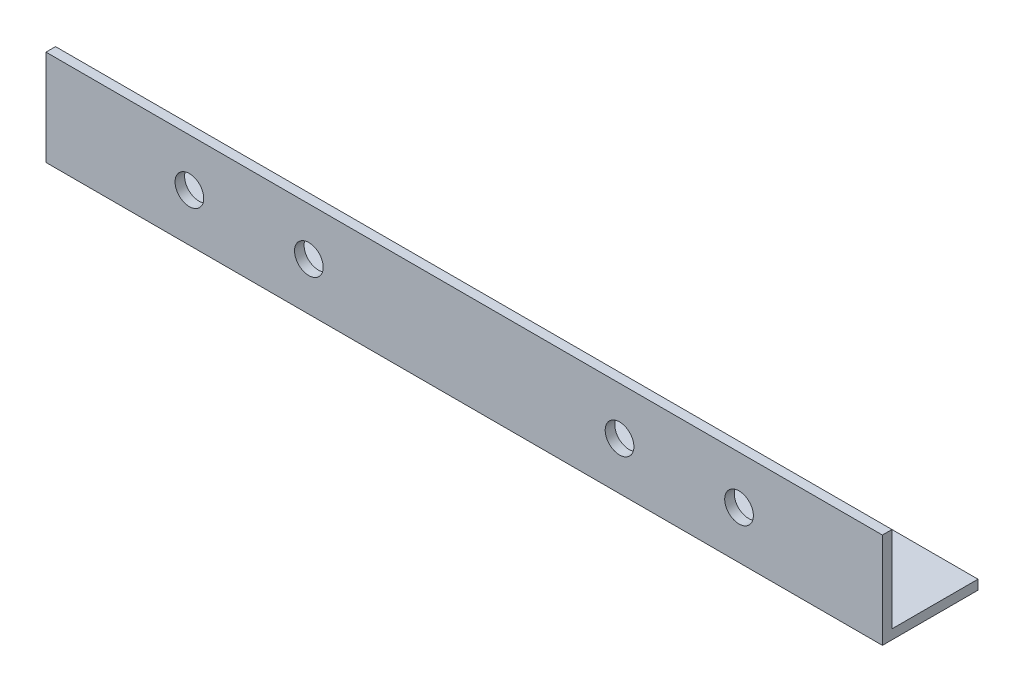
SolidWorks part; units mm, degrees
ref_plane "Front Plane" through (0, 0, 0) normal (0, 0, 1) x (1, 0, 0)
ref_plane "Top Plane" through (0, 0, 0) normal (0, 1, 0) x (1, 0, 0)
ref_plane "Right Plane" through (0, 0, 0) normal (1, 0, 0) x (0, 0, -1)
sketch "Эскиз1" plane through (0, 0, 0) normal (1, 0, 0) x (0, 0, -1)
  line L0 (0, 0) -> (0, 40)
  line L1 (0, 40) -> (4, 40)
  line L2 (4, 40) -> (4, 4)
  line L3 (4, 4) -> (40, 4)
  line L4 (40, 4) -> (40, 0)
  line L5 (40, 0) -> (0, 0)
  dimension "D1" = 40
  dimension "D2" = 40
  dimension "D3" = 4
  dimension "D4" = 4
extrude "Бобышка-Вытянуть1" add sketch "Эскиз1" along normal blind 350
sketch "Эскиз2" plane through (0, 0, 0) normal (0, 0, 1) x (1, 0, 0)
  line L0 (0, 40) -> (0, 0) construction
  line L1 (350, 40) -> (0, 40) construction
  circle A0 centre (60, 20) radius 6
  dimension "D1" = 12
  dimension "D2" = 60
  dimension "D3" = 20
extrude "Вырез-Вытянуть1" cut sketch "Эскиз2" against normal through all
sketch "Эскиз3" plane through (0, 0, 0) normal (0, 0, 1) x (1, 0, 0)
  line L0 (350, 40) -> (0, 40) construction
  line L1 (350, 40) -> (350, 0) construction
  circle A0 centre (290, 20) radius 6
  dimension "D1" = 20
  dimension "D2" = 60
extrude "Вырез-Вытянуть2" cut sketch "Эскиз3" against normal through all
sketch "Эскиз4" plane through (0, 0, 0) normal (0, 0, 1) x (1, 0, 0)
  line L0 (350, 40) -> (0, 40) construction
  line L2 (0, 40) -> (0, 0) construction
  circle A0 centre (240, 20) radius 6
  point P6 (0, 15.3148)
  dimension "D1" = 20
  dimension "D2" = 240
extrude "Вырез-Вытянуть3" cut sketch "Эскиз4" against normal through all
sketch "Эскиз6" plane through (0, 0, 0) normal (0, 0, 1) x (1, 0, 0)
  line L0 (350, 40) -> (0, 40) construction
  line L1 (350, 40) -> (350, 0) construction
  circle A0 centre (110, 20) radius 6
  dimension "D1" = 20
  dimension "D2" = 240
extrude "Вырез-Вытянуть4" cut sketch "Эскиз6" against normal through all
